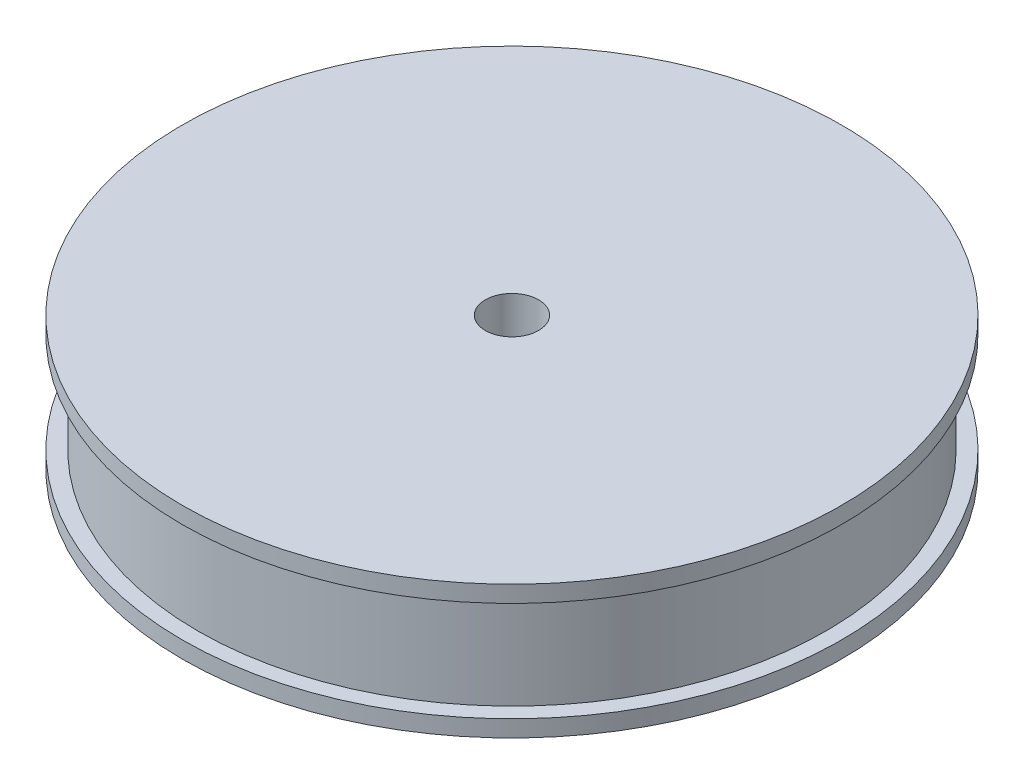
SolidWorks part; units mm, degrees
material "Lega 1060"
ref_plane "Piano frontale" through (0, 0, 0) normal (0, 0, 1) x (1, 0, 0)
ref_plane "Piano superiore" through (0, 0, 0) normal (0, 1, 0) x (1, 0, 0)
ref_plane "Piano destro" through (0, 0, 0) normal (1, 0, 0) x (0, 0, -1)
sketch "Schizzo1" plane through (0, 0, 0) normal (0, 0, 1) x (1, 0, 0)
  line L0 (0, 12.3387) -> (0, -16.129) construction
  line L1 (4, -7.6613) -> (49.5, -7.6613)
  line L2 (49.5, -7.6613) -> (49.5, -5.1613)
  line L3 (49.5, -5.1613) -> (47.175, -5.1613)
  line L4 (47.175, -5.1613) -> (47.175, 9.8387)
  line L5 (47.175, 9.8387) -> (49.5, 9.8387)
  line L6 (49.5, 9.8387) -> (49.5, 12.3387)
  line L7 (49.5, 12.3387) -> (4, 12.3387)
  line L8 (4, 12.3387) -> (4, -7.6613)
  dimension "D1" = 20
  dimension "D2" = 15
  dimension "D3" = 4
  dimension "D4" = 49.5
  dimension "D5" = 47.175
revolve "Rivoluzione1" add sketch "Schizzo1" angle 360 about L0
